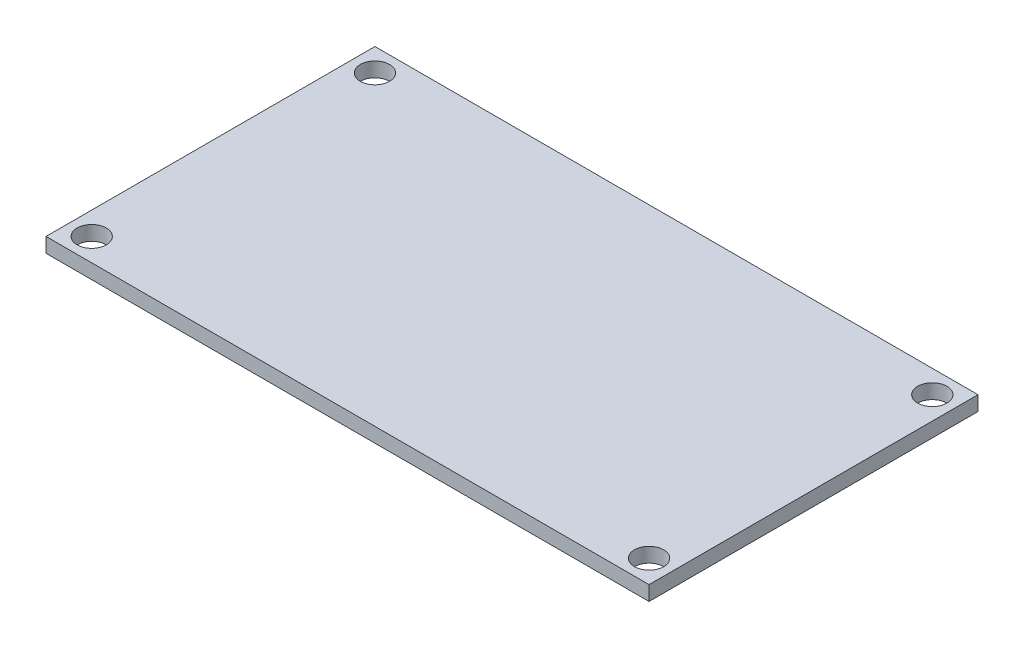
SolidWorks part; units mm, degrees
ref_plane "Front Plane" through (0, 0, 0) normal (0, 0, 1) x (1, 0, 0)
ref_plane "Top Plane" through (0, 0, 0) normal (0, 1, 0) x (1, 0, 0)
ref_plane "Right Plane" through (0, 0, 0) normal (1, 0, 0) x (0, 0, -1)
sketch "BaseS" plane through (0, 0, 0) normal (0, 1, 0) x (1, 0, 0)
  line L1 (-33, 18) -> (33, 18)
  line L2 (-33, 18) -> (-33, -18)
  line L3 (-33, -18) -> (33, -18)
  line L4 (33, 18) -> (33, -18)
  line L5 (-33, 18) -> (33, -18) construction
  line L6 (-33, -18) -> (33, 18) construction
  point P0 (0, 0)
  dimension "Width" = 36
  dimension "Length" = 66
extrude "Base" add sketch "BaseS" along normal blind 1.6
hole_wizard "M3 Clearance Hole1" positions "Sketch2" profile "Sketch3" hole size "M3" standard "ANSI Metric" end condition through all
sketch "Sketch2" plane through (0, 1.6, 0) normal (0, 1, 0) x (1, 0, 0)
  point P0 (-30.5, 15.5)
  dimension "D1" = 15.5
  dimension "D2" = 30.5
sketch "Sketch3" plane through (-30.5, 1.6, -15.5) normal (1, 0, 0) x (0, 0, 1)
  line L0 (0, 0) -> (0, 1.6)
  line L1 (0, 1.6) -> (1.6, 1.6)
  line L2 (1.6, 1.6) -> (1.6, 0)
  line L5 (1.6, 0) -> (0, 0)
  line L11 (0, -6.35) -> (0, 107.95) construction
  dimension "Thru Hole Dia." = 3.2
  dimension "Thru Hole Depth" = 1.6
mirror "Mirror1" about plane through (0, 0, 0) normal (1, 0, 0) of "M3 Clearance Hole1"
mirror "Mirror2" about plane through (0, 0, 0) normal (0, 0, 1) of "Mirror1", "M3 Clearance Hole1"
